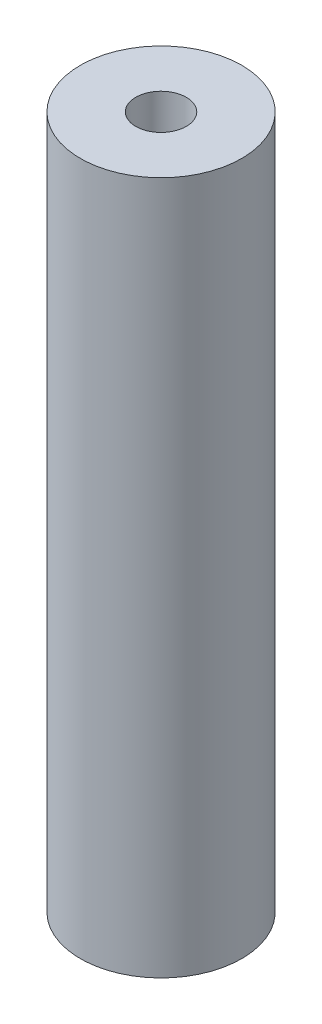
SolidWorks part; units mm, degrees
ref_plane "前视基准面" through (0, 0, 0) normal (0, 0, 1) x (1, 0, 0)
ref_plane "上视基准面" through (0, 0, 0) normal (0, 1, 0) x (1, 0, 0)
ref_plane "右视基准面" through (0, 0, 0) normal (1, 0, 0) x (0, 0, -1)
other "Configuration Table"
sketch "草图1" plane through (0, 0, 0) normal (0, 1, 0) x (1, 0, 0)
  circle A0 centre (0, 0) radius 4.725
  circle A1 centre (0, 0) radius 1.55
  dimension "D1" = 9.45
  dimension "D2" = 3.1
extrude "凸台-拉伸1" add sketch "草图1" along normal blind 42.5
sketch "草图2" plane through (0, 42.5, 0) normal (0, 1, 0) x (1, 0, 0)
  circle A0 centre (0, 0) radius 4.85
  circle A1 centre (0, 0) radius 4.725
  dimension "D1" = 9.7
extrude "凸台-拉伸2" add sketch "草图2" against normal blind 42.5
sketch "草图3" plane through (0, 0, 0) normal (0, -1, 0) x (1, 0, 0)
  circle A0 centre (0, 0) radius 4.85
  circle A1 centre (0, 0) radius 4.875
  dimension "D1" = 9.75
extrude "凸台-拉伸3" add sketch "草图3" against normal blind 42.5
sketch "草图4" plane through (0, 0, 0) normal (0, -1, 0) x (1, 0, 0)
  circle A0 centre (0, 0) radius 4.875
  circle A1 centre (0, 0) radius 4.95
  dimension "D1" = 9.9
extrude "凸台-拉伸4" add sketch "草图4" against normal blind 42.5
